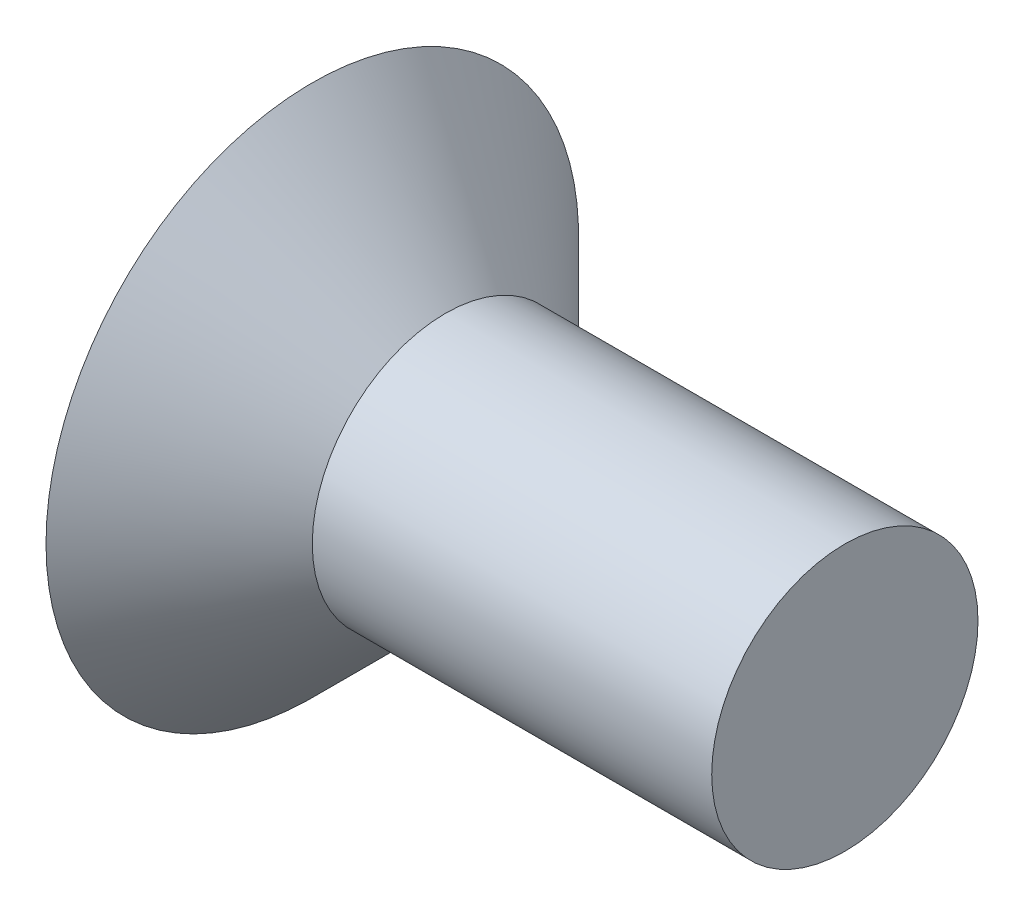
SolidWorks part; units mm, degrees
material "普通碳钢"
ref_plane "前视基准面" through (0, 0, 0) normal (0, 0, 1) x (1, 0, 0)
ref_plane "上视基准面" through (0, 0, 0) normal (0, 1, 0) x (1, 0, 0)
ref_plane "右视基准面" through (0, 0, 0) normal (1, 0, 0) x (0, 0, -1)
sketch "草图1" plane through (0, 0, 0) normal (0, 0, 1) x (1, 0, 0)
  line L0 (0, 0) -> (0, 3)
  line L5 (0, 0) -> (6, 0) construction
  line L6 (6, 0) -> (6, 1.5)
  line L7 (6, 1.5) -> (1.5, 1.5)
  line L8 (1.5, 1.5) -> (0, 3)
  dimension "D1" = 3
  dimension "D2" = 6
  dimension "D3" = 6
  dimension "D5" = 45
revolve "旋转1" add sketch "草图1" angle 360 about L5
cosmetic thread "装饰螺纹线2" parameters "D2"=1.221
sketch "草图2" plane through (0, 0, 0) normal (-1, 0, 0) x (0, 0, 1)
  line L1 (0, 1.1547) -> (-1, 0.5774)
  line L2 (-1, 0.5774) -> (-1, -0.5774)
  line L3 (-1, -0.5774) -> (0, -1.1547)
  line L4 (0, -1.1547) -> (1, -0.5774)
  line L5 (1, -0.5774) -> (1, 0.5774)
  line L6 (1, 0.5774) -> (0, 1.1547)
  circle A0 centre (0, 0) radius 1 construction
  dimension "D1" = 1
extrude "切除-拉伸1" cut sketch "草图2" against normal blind 1
